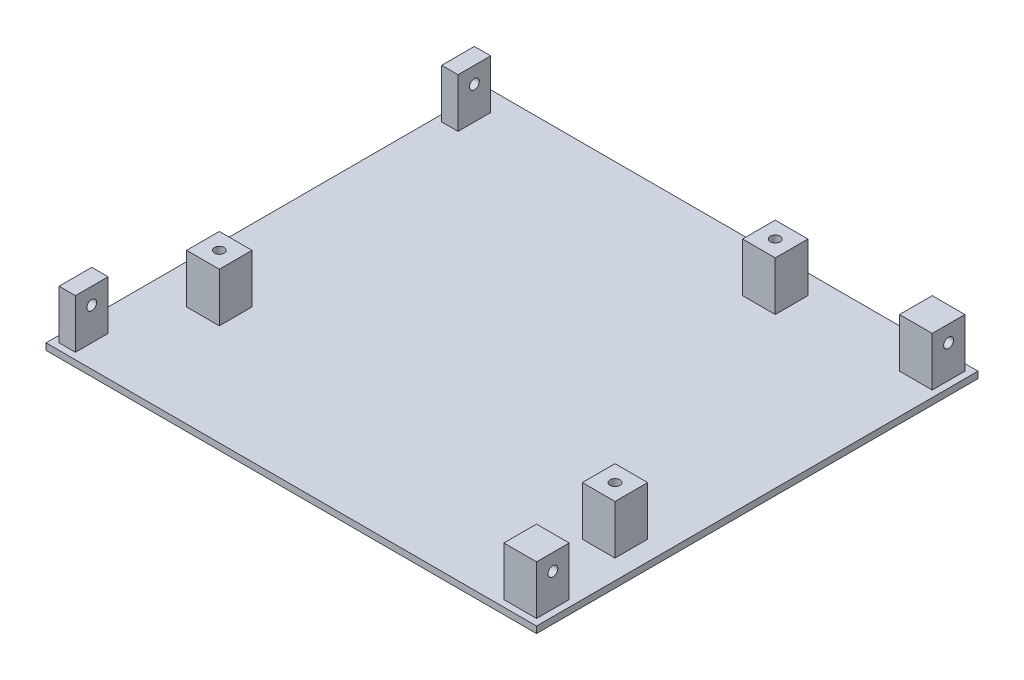
SolidWorks part; units mm, degrees
ref_plane "Alzado" through (0, 0, 0) normal (0, 0, 1) x (1, 0, 0)
ref_plane "Planta" through (0, 0, 0) normal (0, 1, 0) x (1, 0, 0)
ref_plane "Vista lateral" through (0, 0, 0) normal (1, 0, 0) x (0, 0, -1)
sketch "Croquis6" plane through (0, 0, 0) normal (0, 1, 0) x (1, 0, 0)
  line L0 (0, 129) -> (144, 129) construction
  line L1 (0, 0) -> (150, 0)
  line L2 (0, 0) -> (0, 135)
  line L3 (0, 135) -> (150, 135)
  line L4 (150, 0) -> (150, 135)
  line L5 (144, 129) -> (144, 0) construction
  line L6 (0, 133) -> (148, 133) construction
  line L7 (148, 133) -> (148, 0) construction
  line L8 (0, 40) -> (22, 40) construction
  line L9 (0, 129) -> (5, 129)
  line L10 (0, 129) -> (0, 119)
  line L11 (0, 119) -> (5, 119)
  line L12 (5, 129) -> (5, 119)
  line L13 (0, 0) -> (5, 0)
  line L14 (0, 0) -> (0, 10)
  line L15 (0, 10) -> (5, 10)
  line L16 (5, 0) -> (5, 10)
  line L21 (148, 133) -> (138, 133)
  line L22 (148, 133) -> (148, 123)
  line L23 (148, 123) -> (138, 123)
  line L24 (138, 133) -> (138, 123)
  line L25 (150, 0) -> (140, 0)
  line L26 (150, 0) -> (150, 10)
  line L27 (150, 10) -> (140, 10)
  line L28 (140, 0) -> (140, 10)
  line L29 (94, 129) -> (104, 129)
  line L30 (94, 129) -> (94, 119)
  line L31 (94, 119) -> (104, 119)
  line L32 (104, 129) -> (104, 119)
  line L33 (144, 40) -> (134, 40)
  line L34 (144, 40) -> (144, 30)
  line L35 (144, 30) -> (134, 30)
  line L36 (134, 40) -> (134, 30)
  line L37 (22, 40) -> (22, 0) construction
  line L39 (22, 40) -> (12, 40)
  line L40 (22, 40) -> (22, 30)
  line L41 (22, 30) -> (12, 30)
  line L42 (12, 40) -> (12, 30)
  circle A0 centre (99, 124) radius 1.5
  circle A1 centre (139, 35) radius 1.5
  circle A2 centre (17, 35) radius 1.5
  point P31 (139, 30)
  dimension "D24" = 3
  dimension "D25" = 3
  dimension "D26" = 3
  dimension "D1" = 135
  dimension "D2" = 150
  dimension "D3" = 6
  dimension "D4" = 6
  dimension "D5" = 2
  dimension "D6" = 2
  dimension "D7" = 5
  dimension "D8" = 10
  dimension "D9" = 10
  dimension "D10" = 5
  dimension "D11" = 10
  dimension "D12" = 10
  dimension "D13" = 10
  dimension "D14" = 10
  dimension "D15" = 10
  dimension "D16" = 10
  dimension "D17" = 40
  dimension "D18" = 30
  dimension "D19" = 10
  dimension "D20" = 10
  dimension "D21" = 22
  dimension "D22" = 10
  dimension "D23" = 10
  dimension "D27" = 5
  dimension "D28" = 5
  dimension "D29" = 5
  dimension "D30" = 5
  dimension "D31" = 5
  dimension "D32" = 5
extrude "Saliente-Extruir6" add sketch "Croquis6" against normal blind 2 contours L2 L1 L4 L3
sketch "Croquis8" plane through (0, 0, 0) normal (0, 1, 0) x (1, 0, 0)
  line L0 (0, 133) -> (148, 133) construction
  line L1 (0, 0) -> (0, 135) construction
  line L2 (148, 133) -> (148, 2) construction
  line L3 (0, 0) -> (150, 0) construction
  line L4 (2, 129) -> (144, 129) construction
  line L5 (144, 129) -> (144, 0) construction
  line L6 (0, 135) -> (150, 135) construction
  line L7 (150, 0) -> (150, 135) construction
  line L8 (0, 41) -> (22, 41) construction
  line L9 (2, 129) -> (7, 129)
  line L11 (2, 119) -> (7, 119)
  line L12 (7, 129) -> (7, 119)
  line L15 (2, 12) -> (7, 12)
  line L16 (7, 2) -> (7, 12)
  line L17 (148, 133) -> (138, 133)
  line L18 (148, 133) -> (148, 123)
  line L19 (148, 123) -> (138, 123)
  line L20 (138, 133) -> (138, 123)
  line L22 (148, 2) -> (148, 12)
  line L23 (148, 12) -> (138, 12)
  line L24 (138, 2) -> (138, 12)
  line L25 (22, 41) -> (22, 0) construction
  line L26 (2, 119) -> (2, 129)
  line L27 (144, 30) -> (134, 30)
  line L28 (144, 30) -> (144, 40)
  line L29 (144, 40) -> (134, 40)
  line L30 (134, 30) -> (134, 40)
  line L31 (22, 41) -> (12, 41)
  line L32 (22, 41) -> (22, 31)
  line L33 (22, 31) -> (12, 31)
  line L34 (12, 41) -> (12, 31)
  line L35 (94, 129) -> (104, 129)
  line L36 (94, 129) -> (94, 119)
  line L37 (94, 119) -> (104, 119)
  line L38 (104, 129) -> (104, 119)
  line L39 (2, 2) -> (2, 12)
  line L40 (2, 2) -> (7, 2)
  line L41 (138, 2) -> (148, 2)
  circle A0 centre (17, 36) radius 1.5
  circle A1 centre (139, 35) radius 1.5
  circle A2 centre (99, 124) radius 1.5
  point P46 (104, 124)
  dimension "D22" = 3
  dimension "D25" = 3
  dimension "D31" = 3
  dimension "D1" = 2
  dimension "D2" = 2
  dimension "D3" = 4
  dimension "D4" = 4
  dimension "D5" = 10
  dimension "D6" = 2
  dimension "D7" = 5
  dimension "D8" = 2
  dimension "D9" = 10
  dimension "D10" = 10
  dimension "D11" = 10
  dimension "D12" = 10
  dimension "D13" = 41
  dimension "D14" = 22
  dimension "D15" = 10
  dimension "D16" = 10
  dimension "D17" = 30
  dimension "D18" = 10
  dimension "D19" = 10
  dimension "D20" = 5
  dimension "D21" = 5
  dimension "D23" = 5
  dimension "D24" = 5
  dimension "D26" = 10
  dimension "D27" = 10
  dimension "D28" = 40
  dimension "D29" = 5
  dimension "D30" = 5
  dimension "D32" = 5
  dimension "D33" = 2
  dimension "D34" = 10
  dimension "D35" = 2
extrude "Saliente-Extruir7" add sketch "Croquis8" along normal blind 15
sketch "Croquis9" plane through (0, 0, 0) normal (-1, 0, 0) x (0, 0, 1)
  line L4 (-2, 15) -> (-2, 0) construction
  line L5 (-12, 15) -> (-2, 15) construction
  line L6 (-119, 15) -> (-119, 0) construction
  line L7 (-129, 15) -> (-119, 15) construction
  circle A0 centre (-124, 10) radius 1.5
  circle A1 centre (-7, 10) radius 1.5
  dimension "D1" = 3
  dimension "D2" = 3
  dimension "D3" = 5
  dimension "D4" = 5
  dimension "D5" = 5
  dimension "D6" = 5
extrude "Cortar-Extruir1" cut sketch "Croquis9" against normal blind 10
sketch "Croquis10" plane through (148, 0, 0) normal (1, 0, 0) x (0, 0, -1)
  line L0 (12, 15) -> (12, 0) construction
  line L1 (2, 15) -> (12, 15) construction
  line L2 (133, 15) -> (133, 0) construction
  line L3 (123, 15) -> (133, 15) construction
  circle A0 centre (7, 10) radius 1.5
  circle A1 centre (128, 10) radius 1.5
  dimension "D1" = 3
  dimension "D2" = 3
  dimension "D3" = 5
  dimension "D4" = 5
  dimension "D5" = 5
  dimension "D6" = 5
extrude "Cortar-Extruir2" cut sketch "Croquis10" against normal blind 10
